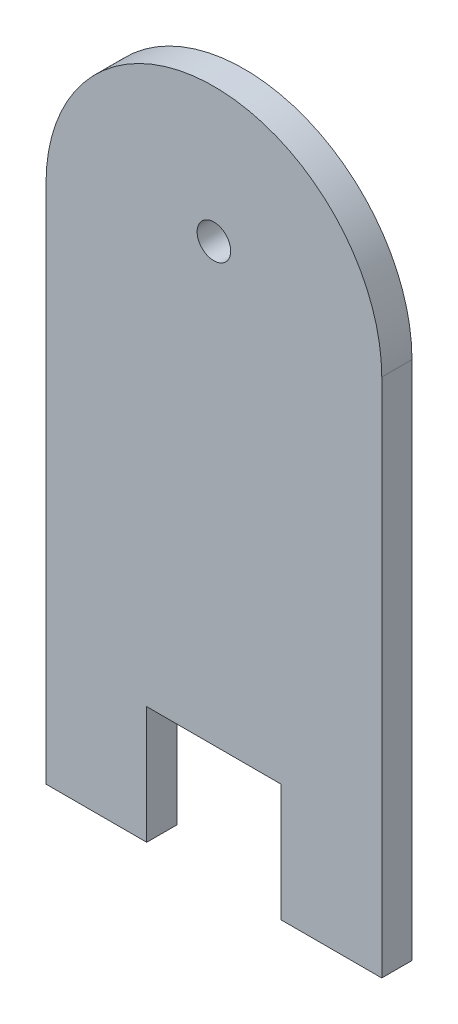
SolidWorks part; units mm, degrees
material "Balsa"
ref_plane "Front Plane" through (0, 0, 0) normal (0, 0, 1) x (1, 0, 0)
ref_plane "Top Plane" through (0, 0, 0) normal (0, 1, 0) x (1, 0, 0)
ref_plane "Right Plane" through (0, 0, 0) normal (1, 0, 0) x (0, 0, -1)
sketch "Sketch1" plane through (0, 0, 0) normal (0, 0, 1) x (1, 0, 0)
  line L9 (-10, -65) -> (-25, -65)
  line L10 (-10, -65) -> (-10, -72.5)
  line L11 (-10, -72.5) -> (-25, -72.5)
  line L12 (-25, -65) -> (-25, -72.5)
  line L13 (-25, 5) -> (25, 5)
  line L14 (-25, 5) -> (-25, -55)
  line L15 (-25, -55) -> (25, -55)
  line L16 (25, 5) -> (25, -55)
  line L17 (-25, -55) -> (-10, -55)
  line L18 (-25, -55) -> (-25, -65)
  line L19 (-25, -65) -> (-10, -65)
  line L20 (-10, -55) -> (-10, -65)
  line L21 (25, -55) -> (10, -55)
  line L22 (25, -55) -> (25, -65)
  line L23 (25, -65) -> (10, -65)
  line L24 (10, -55) -> (10, -65)
  line L25 (25, -65) -> (10, -65)
  line L26 (25, -65) -> (25, -72.5)
  line L27 (25, -72.5) -> (10, -72.5)
  line L28 (10, -65) -> (10, -72.5)
  arc A4 (25, 5) -> (-25, 5) centre (0, 5) ccw
  point P1 (0, 30)
  point P30 (0, -55)
  dimension "D2" = 95
  dimension "D3" = 5
  dimension "D4" = 7.5
  dimension "D5" = 7.5
  dimension "D10" = 50
  dimension "D13" = 15
  dimension "D14" = 15
  dimension "D15" = 10
extrude "Boss-Extrude1" add sketch "Sketch1" along normal blind 4.5
sketch "Sketch2" plane through (0, 0, 4.5) normal (0, 0, 1) x (1, 0, 0)
  circle A0 centre (0, 10) radius 2.5
  arc A1 (25, 5) -> (-25, 5) centre (0, 5) ccw construction
  point P5 (0, 30)
  dimension "D2" = 5
  dimension "D1" = 20
extrude "Cut-Extrude1" cut sketch "Sketch2" against normal blind 10
